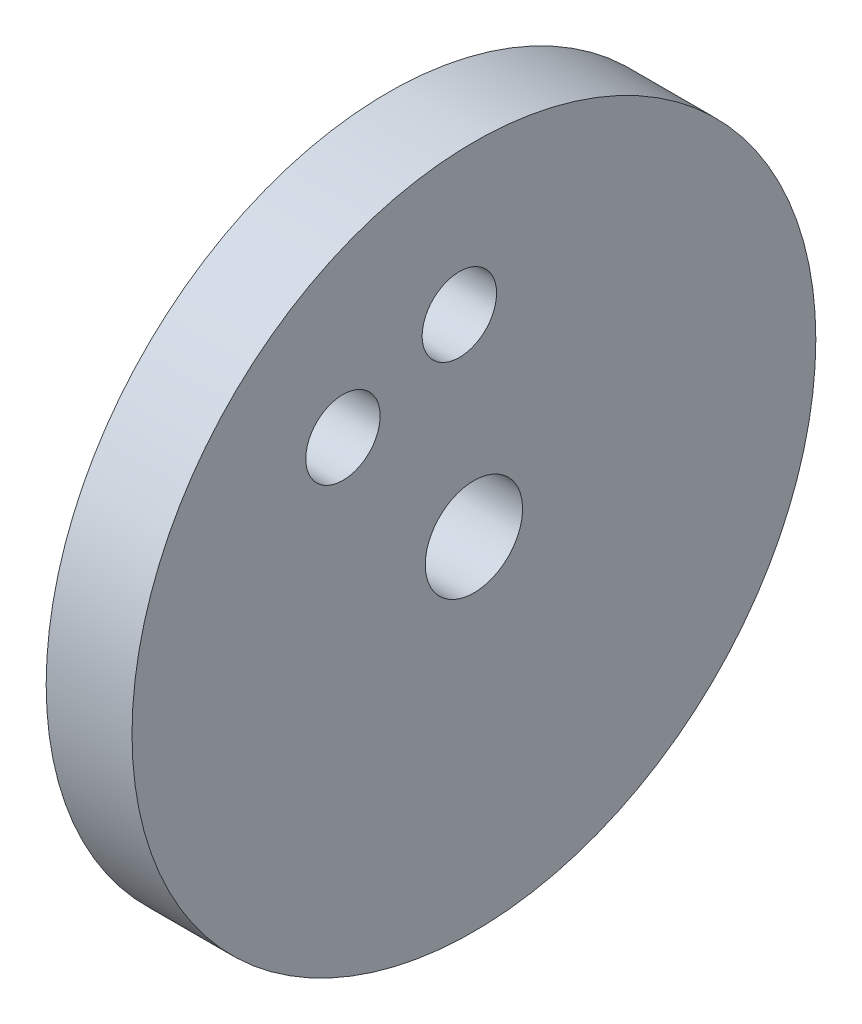
SolidWorks part; units mm, degrees
ref_plane "Front Plane" through (0, 0, 0) normal (0, 0, 1) x (1, 0, 0)
ref_plane "Top Plane" through (0, 0, 0) normal (0, 1, 0) x (1, 0, 0)
ref_plane "Right Plane" through (0, 0, 0) normal (1, 0, 0) x (0, 0, -1)
sketch "Axial profile (mm)" plane through (0, 0, 0) normal (0, 0, 1) x (1, 0, 0)
  line L0 (-110, 0) -> (75, 0) construction
  line L1 (73, 3.4) -> (79, 3.4)
  line L2 (79, 3.4) -> (79, 23.9)
  line L3 (79, 23.9) -> (73, 23.9)
  line L4 (73, 23.9) -> (73, 3.4)
revolve "Full revolution" add sketch "Axial profile (mm)" angle 360 about L0
sketch "Sketch2" plane through (0, 0, 0) normal (1, 0, 0) x (0, 0, -1)
  circle A0 centre (-1.0169, 13.963) radius 2.6
  circle A1 centre (-9.1543, 10.5924) radius 2.6
extrude "Axial holes" cut sketch "Sketch2" against normal through all and the other way through all
